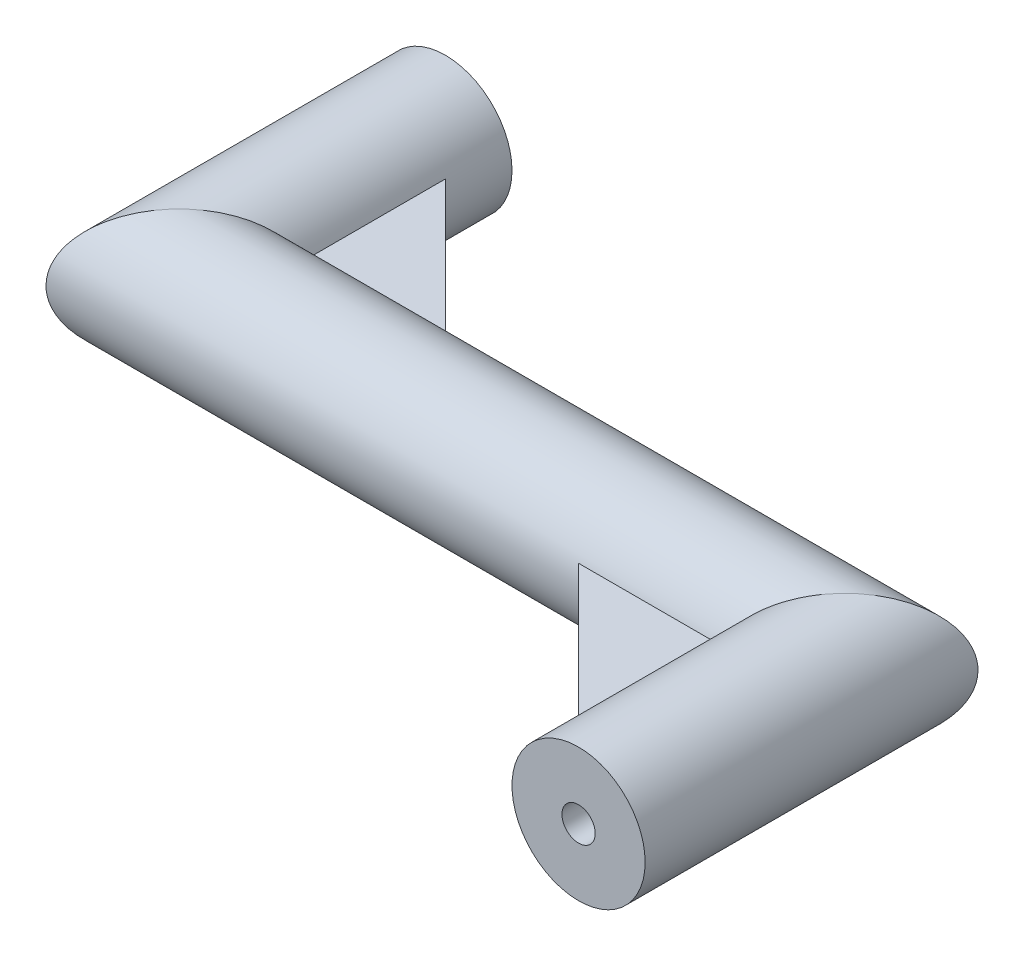
SolidWorks part; units mm, degrees
ref_plane "Front Plane" through (0, 0, 0) normal (0, 0, 1) x (1, 0, 0)
ref_plane "Top Plane" through (0, 0, 0) normal (0, 1, 0) x (1, 0, 0)
ref_plane "Right Plane" through (0, 0, 0) normal (1, 0, 0) x (0, 0, -1)
sketch "Sketch1" plane through (0, 0, 0) normal (0, 0, 1) x (1, 0, 0)
  circle A0 centre (0, 0) radius 3
  dimension "D1" = 6
sketch "Sketch3" plane through (0, 0, 0) normal (0, 1, 0) x (1, 0, 0)
  line L0 (0, 0) -> (0, 12)
  line L1 (0, 12) -> (-30, 12)
  line L2 (-30, 12) -> (-30, 24)
  dimension "D1" = 12
  dimension "D2" = 12
  dimension "D3" = 30
sweep "Sweep1" add profiles "Sketch1" path "Sketch3"
sketch "Sketch4" plane through (0, 0, 0) normal (0, 1, 0) x (1, 0, 0)
  line L0 (0, 0) -> (0, 12) construction
  line L1 (0, 12) -> (-30, 12) construction
  line L2 (-30, 12) -> (-30, 24) construction
  line L3 (0, 0) -> (0, 12)
  line L4 (0, 12) -> (-30, 12)
  line L5 (-30, 12) -> (-30, 24)
  line L6 (-30, 24) -> (-18, 12)
  line L7 (0, 0) -> (-12, 12)
  dimension "D1" = 45
  dimension "D2" = 45
extrude "Boss-Extrude1" add sketch "Sketch4" along normal mid plane 2 contours L6 L5 L4 | L7 L3 L4
sketch "Sketch5" plane through (0, 0, 0) normal (0, 0, 1) x (1, 0, 0)
  circle A0 centre (0, 0) radius 0.75
  dimension "D1" = 1.5
extrude "Cut-Extrude1" cut sketch "Sketch5" against normal blind 10
sketch "Sketch6" plane through (0, 0, -24) normal (0, 0, -1) x (-1, 0, 0)
  circle A0 centre (30, 0) radius 0.75
  dimension "D1" = 1.5
extrude "Cut-Extrude2" cut sketch "Sketch6" against normal blind 10
